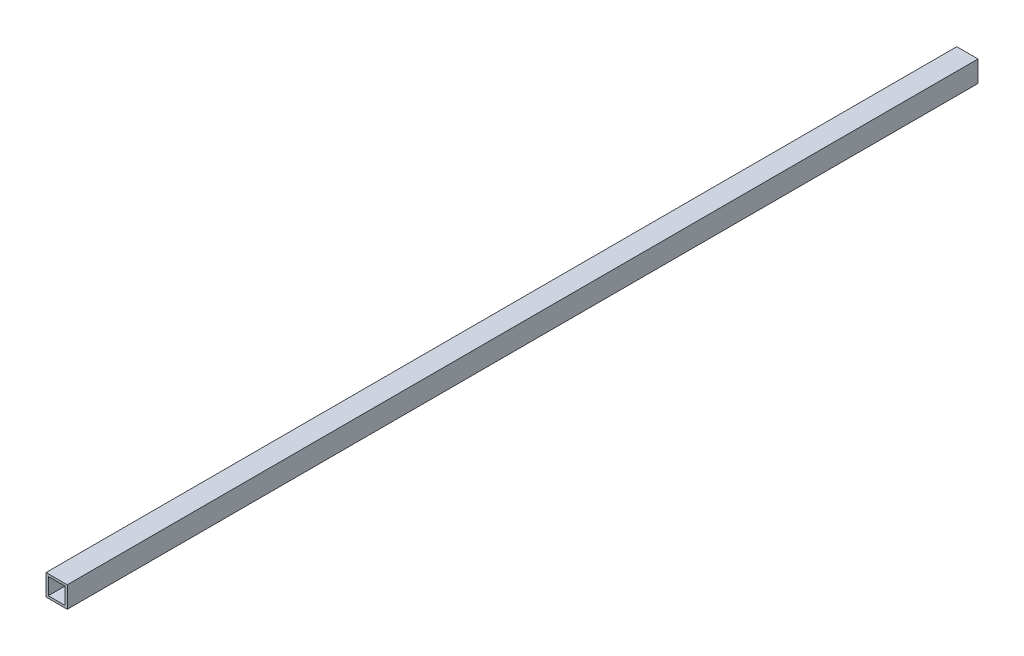
SolidWorks part; units mm, degrees
ref_plane "前视基准面" through (0, 0, 0) normal (0, 0, 1) x (1, 0, 0)
ref_plane "上视基准面" through (0, 0, 0) normal (0, 1, 0) x (1, 0, 0)
ref_plane "右视基准面" through (0, 0, 0) normal (1, 0, 0) x (0, 0, -1)
sketch "草图1" plane through (0, 0, 0) normal (0, 0, 1) x (1, 0, 0)
  line L1 (-5.5, 5.5) -> (5.5, 5.5)
  line L2 (-5.5, 5.5) -> (-5.5, -5.5)
  line L3 (-5.5, -5.5) -> (5.5, -5.5)
  line L4 (5.5, 5.5) -> (5.5, -5.5)
  line L5 (-5.5, 5.5) -> (5.5, -5.5) construction
  line L6 (-5.5, -5.5) -> (5.5, 5.5) construction
  point P0 (0, 0)
  dimension "D1" = 11
extrude "拉伸-薄壁1" add sketch "草图1" along normal blind 600 thin thin type one direction wall 1.5
